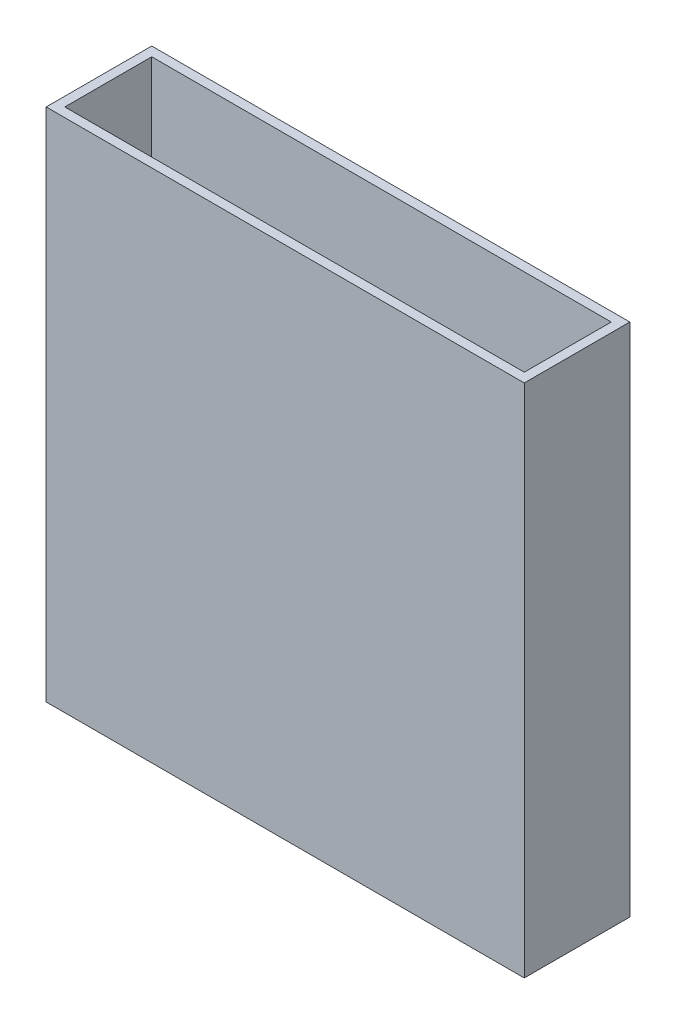
SolidWorks part; units mm, degrees
ref_plane "Plan de face" through (0, 0, 0) normal (0, 0, 1) x (1, 0, 0)
ref_plane "Plan de dessus" through (0, 0, 0) normal (0, 1, 0) x (1, 0, 0)
ref_plane "Plan de droite" through (0, 0, 0) normal (1, 0, 0) x (0, 0, -1)
sketch "Esquisse1" plane through (0, 0, 0) normal (0, 1, 0) x (1, 0, 0)
  line L1 (-38.5, -8.5) -> (38.5, -8.5)
  line L2 (-38.5, -8.5) -> (-38.5, 8.5)
  line L3 (-38.5, 8.5) -> (38.5, 8.5)
  line L4 (38.5, -8.5) -> (38.5, 8.5)
  line L5 (-38.5, -8.5) -> (38.5, 8.5) construction
  line L6 (-38.5, 8.5) -> (38.5, -8.5) construction
  point P0 (0, 0)
  dimension "D1" = 17
  dimension "D2" = 77
extrude "Boss.-Extru.1" add sketch "Esquisse1" along normal blind 83 contours L3 L4 L1 L2
sketch "Esquisse2" plane through (0, 83, 0) normal (0, 1, 0) x (1, 0, 0)
  line L1 (-37, -7) -> (37, -7)
  line L2 (-37, -7) -> (-37, 7)
  line L3 (-37, 7) -> (37, 7)
  line L4 (37, -7) -> (37, 7)
  line L5 (-37, -7) -> (37, 7) construction
  line L6 (-37, 7) -> (37, -7) construction
  point P0 (0, 0)
  dimension "D1" = 74
  dimension "D2" = 14
extrude "Enlèv. mat.-Extru.1" cut sketch "Esquisse2" against normal blind 80 contours L3 L4 L1 L2
